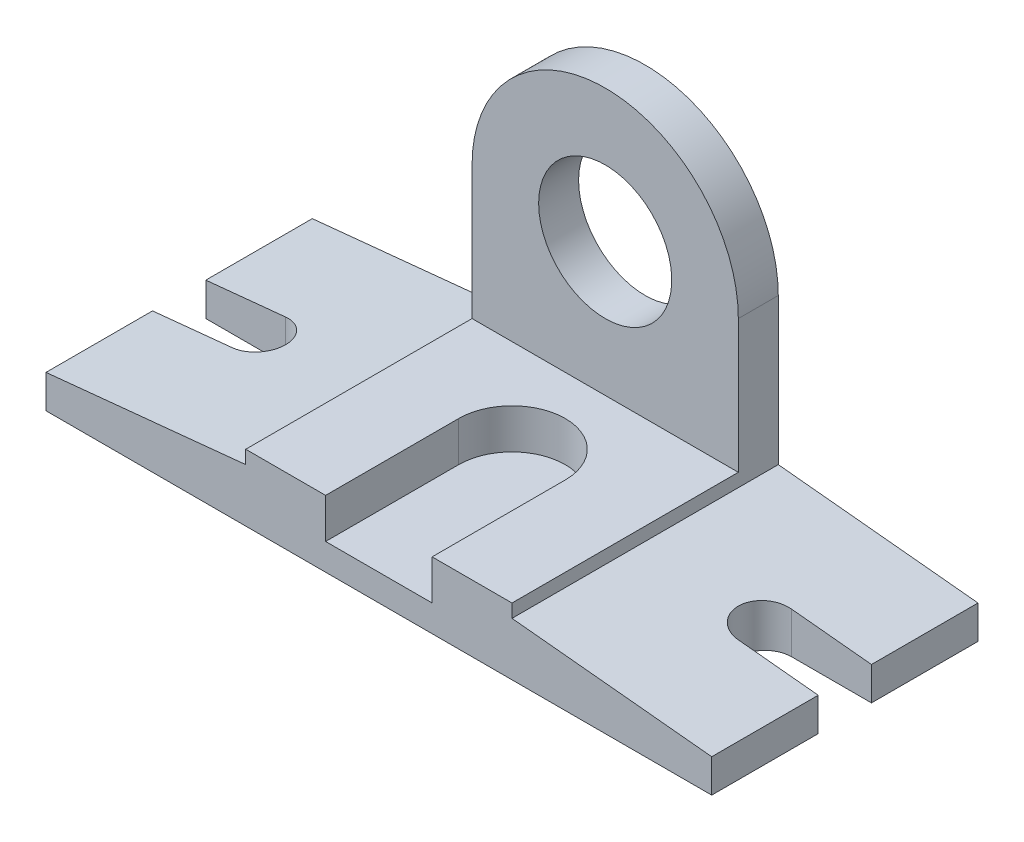
SolidWorks part; units mm, degrees
ref_plane "Front Plane" through (0, 0, 0) normal (0, 0, 1) x (1, 0, 0)
ref_plane "Top Plane" through (0, 0, 0) normal (0, 1, 0) x (1, 0, 0)
ref_plane "Right Plane" through (0, 0, 0) normal (1, 0, 0) x (0, 0, -1)
sketch "Sketch2" plane through (0, 0, 0) normal (0, 0, 1) x (1, 0, 0)
  line L0 (-250, 0) -> (250, 0)
  line L1 (0, 0) -> (0, 232.7381) construction
  line L2 (-250, 0) -> (-250, 25)
  line L3 (-100, 50) -> (100, 50)
  line L4 (-100, 50) -> (-100, 40)
  line L5 (-100, 40) -> (-250, 25)
  line L6 (100, 50) -> (100, 40)
  line L7 (100, 40) -> (250, 25)
  line L8 (250, 25) -> (250, 0)
  dimension "D1" = 500
  dimension "D2" = 25
  dimension "D3" = 200
  dimension "D4" = 50
  dimension "D5" = 10
extrude "Boss-Extrude1" add sketch "Sketch2" against normal blind 200
sketch "Sketch3" plane through (0, 50, 0) normal (0, 1, 0) x (1, 0, 0)
  line L0 (100, 0) -> (-100, 0) construction
  line L1 (-40, 100) -> (-40, 0)
  line L2 (40, 100) -> (40, 0)
  line L3 (40, 0) -> (-40, 0)
  arc A0 (40, 100) -> (-40, 100) centre (0, 100) ccw
  dimension "D1" = 80
  dimension "D2" = 100
extrude "Cut-Extrude1" cut sketch "Sketch3" against normal blind 30
sketch "Sketch4" plane through (0, 0, 0) normal (0, -1, 0) x (1, 0, 0)
  line L0 (-250, -200) -> (-250, 0) construction
  line L1 (-190, -80) -> (-250, -80)
  line L2 (-190, -120) -> (-250, -120)
  line L3 (-250, -120) -> (-250, -80)
  line L4 (0, 0) -> (0, -200) construction
  line L5 (-250, -200) -> (250, -200) construction
  line L6 (250, -120) -> (250, -80)
  line L7 (190, -120) -> (250, -120)
  line L8 (190, -80) -> (250, -80)
  arc A0 (-190, -120) -> (-190, -80) centre (-190, -100) ccw
  arc A1 (190, -120) -> (190, -80) centre (190, -100) cw
  point P4 (-250, -100)
  dimension "D1" = 60
  dimension "D2" = 40
extrude "Cut-Extrude2" cut sketch "Sketch4" against normal through all
sketch "Sketch5" plane through (0, 0, -200) normal (0, 0, -1) x (-1, 0, 0)
  line L0 (-100, 50) -> (-100, 150)
  line L1 (250, 0) -> (-250, 0) construction
  line L2 (100, 150) -> (100, 50)
  line L3 (100, 50) -> (-100, 50)
  arc A0 (100, 150) -> (-100, 150) centre (0, 150) ccw
  circle A1 centre (0, 150) radius 50
  dimension "D1" = 200
  dimension "D2" = 150
  dimension "D3" = 100
extrude "Boss-Extrude2" add sketch "Sketch5" against normal blind 30
